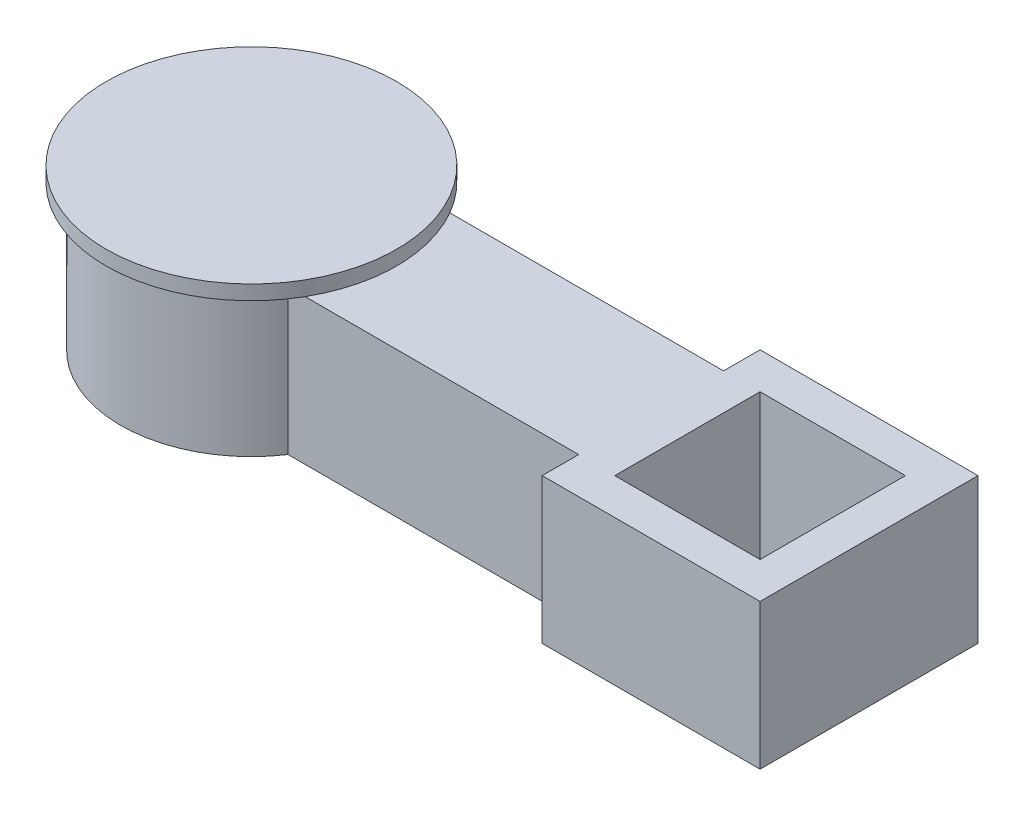
SolidWorks part; units mm, degrees
ref_plane "Front Plane" through (0, 0, 0) normal (0, 0, 1) x (1, 0, 0)
ref_plane "Top Plane" through (0, 0, 0) normal (0, 1, 0) x (1, 0, 0)
ref_plane "Right Plane" through (0, 0, 0) normal (1, 0, 0) x (0, 0, -1)
sketch "Sketch1" plane through (0, 0, 0) normal (0, 1, 0) x (1, 0, 0)
  line L0 (363.1456, 275.7418) -> (363.1456, 275.9924)
  line L1 (363.1456, 175.9924) -> (563.1456, 175.9924)
  line L2 (363.1456, 175.9924) -> (363.1456, 176.2431)
  line L3 (363.1456, 275.9924) -> (563.1456, 275.9924)
  line L4 (563.1456, 175.9924) -> (563.1456, 176.2431)
  line L5 (563.1456, 275.7418) -> (563.1456, 275.9924)
  line L8 (363.1456, 275.9924) -> (563.1456, 275.9924)
  line L9 (363.1456, 275.9924) -> (363.1456, 275.7418)
  line L10 (363.1456, 176.2431) -> (563.1456, 176.2431)
  line L11 (563.1456, 275.9924) -> (563.1456, 176.2431)
  line L12 (563.1456, 301.1178) -> (713.1456, 301.1178)
  line L13 (563.1456, 301.1178) -> (563.1456, 151.1178)
  line L14 (563.1456, 151.1178) -> (713.1456, 151.1178)
  line L15 (713.1456, 301.1178) -> (713.1456, 151.1178)
  arc A0 (363.1456, 275.7418) -> (363.1456, 176.2431) centre (288.1456, 225.9924) ccw
  point P13 (713.1456, 226.1178)
  point P14 (563.1456, 226.1178)
  dimension "D3" = 180
  dimension "D6" = 150
  dimension "D1" = 200
  dimension "D2" = 100
  dimension "D4" = 50
  dimension "D5" = 75
  dimension "D7" = 150
extrude "Boss-Extrude1" add sketch "Sketch1" along normal blind 100 contours L0 A0 L10 L11 L5 L3 | L13 L12 L15 L14
sketch "Sketch5" plane through (0, 100, 0) normal (0, 1, 0) x (1, 0, 0)
  circle A0 centre (288.1456, 225.9924) radius 70
  dimension "D1" = 140
extrude "Cut-Extrude2" cut sketch "Sketch5" against normal blind 100
sketch "Sketch6" plane through (0, 100, 0) normal (0, 1, 0) x (1, 0, 0)
  circle A0 centre (288.1456, 225.9924) radius 100
  dimension "D1" = 200
extrude "Boss-Extrude4" add sketch "Sketch6" along normal blind 10
sketch "Sketch7" plane through (0, 100, 0) normal (0, 1, 0) x (1, 0, 0)
  line L0 (563.1456, 301.1178) -> (713.1456, 301.1178) construction
  line L1 (588.1456, 176.1178) -> (688.1456, 176.1178)
  line L2 (588.1456, 176.1178) -> (588.1456, 276.1178)
  line L3 (588.1456, 276.1178) -> (688.1456, 276.1178)
  line L4 (688.1456, 176.1178) -> (688.1456, 276.1178)
  line L5 (713.1456, 301.1178) -> (713.1456, 151.1178) construction
  point P6 (638.1456, 301.1178)
  point P7 (638.1456, 276.1178)
  point P10 (713.1456, 226.1178)
  point P11 (688.1456, 226.1178)
  dimension "D1" = 100
  dimension "D2" = 100
extrude "Cut-Extrude3" cut sketch "Sketch7" against normal blind 100
sketch "Sketch8" plane through (0, 100, 0) normal (0, 1, 0) x (1, 0, 0)
  line L0 (588.1456, 276.1178) -> (688.1456, 176.1178)
  line L1 (688.1456, 176.1178) -> (688.1456, 276.1178)
  line L2 (688.1456, 276.1178) -> (588.1456, 176.1178)
  line L3 (588.1456, 176.1178) -> (588.1456, 276.1178)
